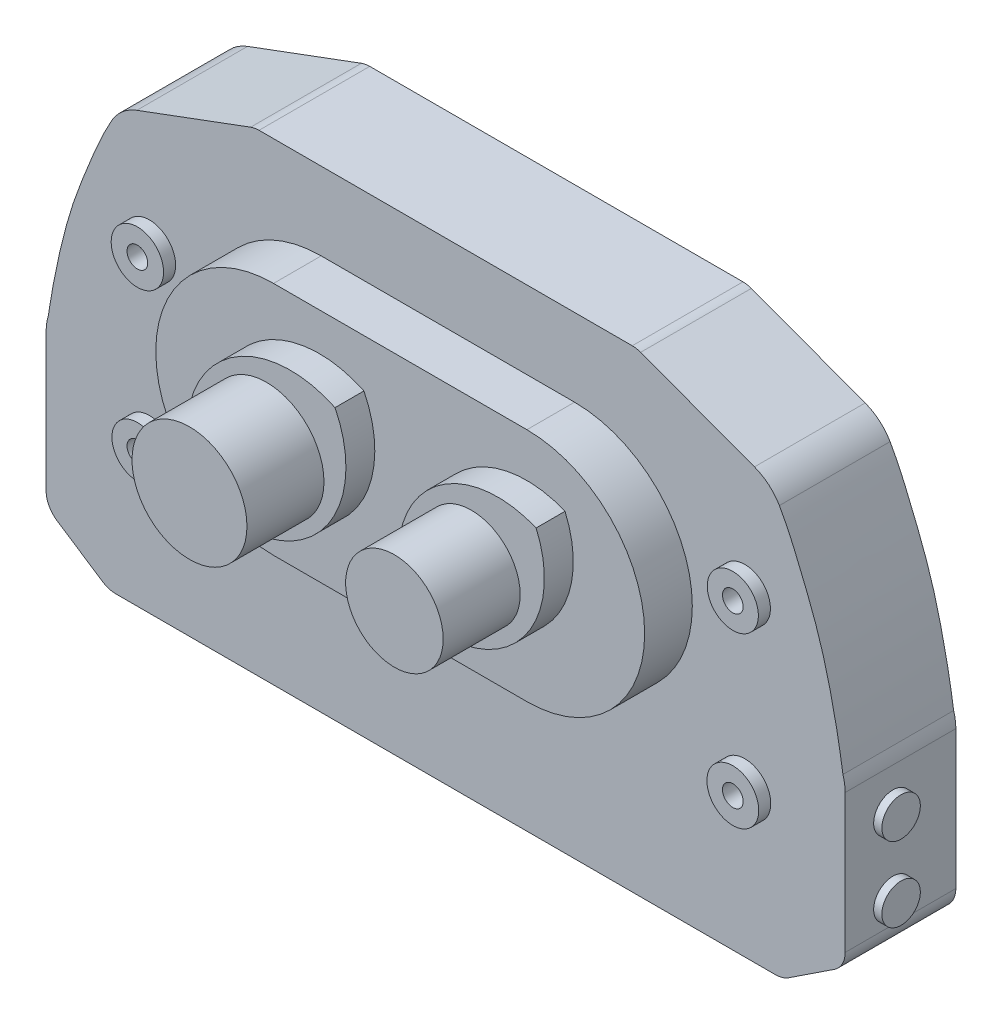
SolidWorks part; units mm, degrees
ref_plane "Front Plane" through (0, 0, 0) normal (0, 0, 1) x (1, 0, 0)
ref_plane "Top Plane" through (0, 0, 0) normal (0, 1, 0) x (1, 0, 0)
ref_plane "Right Plane" through (0, 0, 0) normal (1, 0, 0) x (0, 0, -1)
sketch "Sketch2" plane through (0, 0, 0) normal (0, 0, 1) x (1, 0, 0)
  line L0 (70.5234, -121.2586) -> (80.0018, -115.0085)
  line L1 (82.2493, -110.8343) -> (82.2493, -82.0607)
  line L2 (0, 0) -> (0, 97) construction
  line L3 (122.5391, 337.0673) -> (776.5391, 337.0673) construction
  line L4 (56.1264, 216.4843) -> (710.1264, 216.4843) construction
  line L5 (-39.52, -23.7969) -> (38.0186, -23.7969)
  line L6 (-0.7507, -122.0844) -> (-0.7507, -9.2148) construction
  line L7 (-83.7507, -110.8343) -> (-83.7507, -82.0607)
  line L8 (67.7709, -122.0844) -> (-69.2723, -122.0844)
  line L9 (-72.0248, -121.2586) -> (-81.5032, -115.0085)
  line L10 (-41.261, -24.1098) -> (-64.9089, -32.8935)
  line L11 (39.7596, -24.1098) -> (63.4075, -32.8935)
  line L14 (53.2993, -41.7763) -> (-54.8007, -41.7763) construction
  line L15 (-54.8007, -41.7763) -> (-54.8007, -107.2763) construction
  line L16 (-54.8007, -107.2763) -> (53.2993, -107.2763) construction
  line L17 (53.2993, -107.2763) -> (53.2993, -41.7763) construction
  arc A0 (-70.0862, -37.266) -> (-64.9089, -32.8935) centre (-61.427, -42.2677) cw
  arc A1 (-83.7507, -82.0607) -> (-83.2867, -79.0501) centre (-73.7507, -82.0607) cw
  arc A2 (-81.5032, -115.0085) -> (-83.7507, -110.8343) centre (-78.7507, -110.8343) cw
  arc A3 (-69.2723, -122.0844) -> (-72.0248, -121.2586) centre (-69.2723, -117.0844) cw
  arc A5 (67.7709, -122.0844) -> (70.5234, -121.2586) centre (67.7709, -117.0844) ccw
  arc A6 (80.0018, -115.0085) -> (82.2493, -110.8343) centre (77.2493, -110.8343) ccw
  arc A8 (82.2493, -82.0607) -> (81.7853, -79.0501) centre (72.2493, -82.0607) ccw
  arc A9 (-39.52, -23.7969) -> (-41.261, -24.1098) centre (-39.52, -28.7969) ccw
  arc A10 (68.5848, -37.266) -> (63.4075, -32.8935) centre (59.9256, -42.2677) ccw
  arc A11 (38.0186, -23.7969) -> (39.7596, -24.1098) centre (38.0186, -28.7969) cw
  spline S0 degree 3 poles (-83.2867, -79.0501) (-83.281, -79.0318) (-81.265, -64.2198) (-73.8122, -44.6321) (-71.5907, -39.8705) (-70.0862, -37.266) knots 0.010107 0.010107 0.010107 0.010107 0.430229 0.512694 0.834763 0.834763 0.834763 0.834763
  spline S1 degree 3 poles (81.7853, -79.0501) (81.7796, -79.0318) (79.7636, -64.2198) (72.3108, -44.6321) (70.0893, -39.8705) (68.5848, -37.266) knots 0.010107 0.010107 0.010107 0.010107 0.430229 0.512694 0.834763 0.834763 0.834763 0.834763
  point P5 (0, 0)
  point P13 (-0.7507, -23.7969)
  point P30 (38.9172, -23.7969)
  point P46 (-40.4186, -23.7969)
  point P49 (-0.7507, -41.7763)
  dimension "D1" = 10
  dimension "D2" = 10
  dimension "D3" = 5
  dimension "D4" = 5
  dimension "D5" = 166
  dimension "D6" = 5
extrude "Boss-Extrude1" add sketch "Sketch2" along normal blind 23
sketch "Sketch3" plane through (0, 0, 23) normal (0, 0, 1) x (1, 0, 0)
  line L0 (-0.7507, -23.7969) -> (-0.7507, -122.0844) construction
  line L1 (38.0186, -23.7969) -> (-39.52, -23.7969) construction
  line L2 (-69.2723, -122.0844) -> (67.7709, -122.0844) construction
ref_plane "Plane1" through (-0.7507, 0, 0) normal (-1, 0, 0) x (0, -1, 0)
sketch "Sketch5" plane through (-83.7507, 0, 0) normal (-1, 0, 0) x (0, 0, 1)
  line L0 (-44.9674, 914.2088) -> (400.4847, 914.2088) construction
  line L1 (13.0836, -123.8044) -> (13.0836, -90.5517) construction
  line L2 (-9.5774, -90.5517) -> (13.0836, -90.5517) construction
  line L3 (-9.5774, -106.0696) -> (13.0836, -106.0696) construction
  circle A0 centre (13.0836, -90.5517) radius 4
  circle A1 centre (13.0836, -106.0696) radius 4
extrude "Boss-Extrude3" add sketch "Sketch5" along normal blind 1.7
sketch "Sketch8" plane through (82.2493, 0, 0) normal (1, 0, 0) x (0, 0, -1)
  line L2 (0, -90.5507) -> (-13.08, -90.5507) construction
  line L4 (-13.08, -90.5507) -> (-13.08, -82.0607) construction
  line L6 (-13.08, -90.5507) -> (-13.08, -106.0707) construction
  circle A0 centre (-13.08, -90.5507) radius 4
  circle A1 centre (-13.08, -106.0707) radius 4
extrude "Boss-Extrude4" add sketch "Sketch8" along normal blind 1.7
sketch "Sketch12" plane through (0, 0, 23) normal (0, 0, 1) x (1, 0, 0)
  line L0 (20.3838, 54.9334) -> (416.3838, 54.9334) construction
  line L1 (26.0332, -39.9411) -> (-26.6057, -39.9411)
  line L2 (-26.6057, -39.9411) -> (-26.6057, -88.8696) construction
  line L3 (-26.6057, -88.8696) -> (26.0332, -88.8696)
  line L4 (-0.2862, -39.9411) -> (-0.2862, -88.8696) construction
  arc A0 (-26.6057, -39.9411) -> (-26.6057, -88.8696) centre (-26.6057, -64.4054) ccw
  arc A1 (26.0332, -39.9411) -> (26.0332, -88.8696) centre (26.0332, -64.4054) cw
  circle A2 centre (61.4129, -56.7486) radius 5.3096
  circle A3 centre (61.4129, -91.7846) radius 5.3836
  circle A4 centre (-62.2939, -91.7846) radius 5.291
  circle A5 centre (-62.2939, -56.7486) radius 5.4443
extrude "Boss-Extrude5" add sketch "Sketch12" along normal blind 9.9
sketch "Sketch15" plane through (0, 0, 32.9) normal (0, 0, 1) x (1, 0, 0)
  line L0 (13.4386, 50.6195) -> (409.4386, 50.6195) construction
  line L1 (-7.8316, -49.9018) -> (-36.3069, -78.8976) construction
  line L2 (-0.2862, -39.9411) -> (-0.2862, -88.8696) construction
  line L3 (26.0332, -39.9411) -> (-26.6057, -39.9411) construction
  line L4 (-26.6057, -88.8696) -> (26.0332, -88.8696) construction
  line L5 (-22.0319, -64.3616) -> (20.4621, -64.3616) construction
  line L6 (7.057, -77.9762) -> (33.947, -50.666) construction
  circle A0 centre (-22.0319, -64.3616) radius 11.9456 construction
  arc A1 (-36.3069, -78.8976) -> (-7.8316, -49.9018) centre (-17.0867, -69.2928) cw
  arc A2 (-36.3069, -78.8976) -> (-7.8316, -49.9018) centre (-27.0518, -59.5066) ccw
  circle A3 centre (20.4621, -64.3616) radius 10.1338 construction
  arc A4 (33.947, -50.666) -> (7.057, -77.9762) centre (15.0085, -58.9121) cw
  arc A5 (33.947, -50.666) -> (7.057, -77.9762) centre (25.9955, -69.7301) ccw
extrude "Boss-Extrude6" add sketch "Sketch15" along normal blind 22
sketch "Sketch16" plane through (0, 0, 54.9) normal (0, 0, 1) x (1, 0, 0)
  line L0 (-7.8316, -49.9018) -> (-36.3069, -78.8976) construction
  circle A0 centre (-22.0693, -64.3997) radius 11.94
  arc A1 (-36.3069, -78.8976) -> (-7.8316, -49.9018) centre (-17.0867, -69.2928) cw
  arc A2 (-7.8316, -49.9018) -> (-36.3069, -78.8976) centre (-27.0518, -59.5066) cw
extrude "Cut-Extrude1" cut sketch "Sketch16" against normal blind 16
sketch "Sketch17" plane through (0, 0, 54.9) normal (0, 0, 1) x (1, 0, 0)
  line L0 (33.947, -50.666) -> (7.057, -77.9762) construction
  arc A0 (33.947, -50.666) -> (7.057, -77.9762) centre (25.9955, -69.7301) ccw construction
  arc A1 (7.057, -77.9762) -> (33.947, -50.666) centre (15.0085, -58.9121) ccw construction
  circle A2 centre (20.502, -64.3211) radius 10.13
  arc A3 (7.057, -77.9762) -> (33.947, -50.666) centre (25.9955, -69.7301) cw
  arc A4 (33.947, -50.666) -> (7.057, -77.9762) centre (15.0085, -58.9121) cw
extrude "Cut-Extrude2" cut sketch "Sketch17" against normal blind 16
sketch "Sketch18" plane through (0, 0, 32.9) normal (0, 0, 1) x (1, 0, 0)
  circle A0 centre (61.4129, -56.7486) radius 5.3096
extrude "Cut-Extrude3" cut sketch "Sketch18" against normal blind 7.4
sketch "Sketch19" plane through (0, 0, 32.9) normal (0, 0, 1) x (1, 0, 0)
  circle A0 centre (61.4129, -91.7846) radius 5.3836
extrude "Cut-Extrude4" cut sketch "Sketch19" against normal blind 7.4
sketch "Sketch20" plane through (0, 0, 32.9) normal (0, 0, 1) x (1, 0, 0)
  circle A0 centre (-62.2939, -56.7486) radius 5.4443
extrude "Cut-Extrude5" cut sketch "Sketch20" against normal blind 7.4
sketch "Sketch21" plane through (0, 0, 32.9) normal (0, 0, 1) x (1, 0, 0)
  circle A0 centre (-62.2939, -91.7846) radius 5.291
extrude "Cut-Extrude6" cut sketch "Sketch21" against normal blind 7.4
sketch "Sketch22" plane through (0, 0, 25.5) normal (0, 0, 1) x (1, 0, 0)
  circle A0 centre (-62.2939, -56.7486) radius 2.15
  circle A1 centre (-62.2939, -91.7846) radius 2.15
  circle A2 centre (61.4129, -91.7846) radius 2.15
  circle A3 centre (61.4129, -56.7486) radius 2.15
  dimension "D1" = 4.3
  dimension "D2" = 4.3
  dimension "D3" = 4.3
  dimension "D4" = 4.3
extrude "Cut-Extrude7" cut sketch "Sketch22" against normal blind 10
